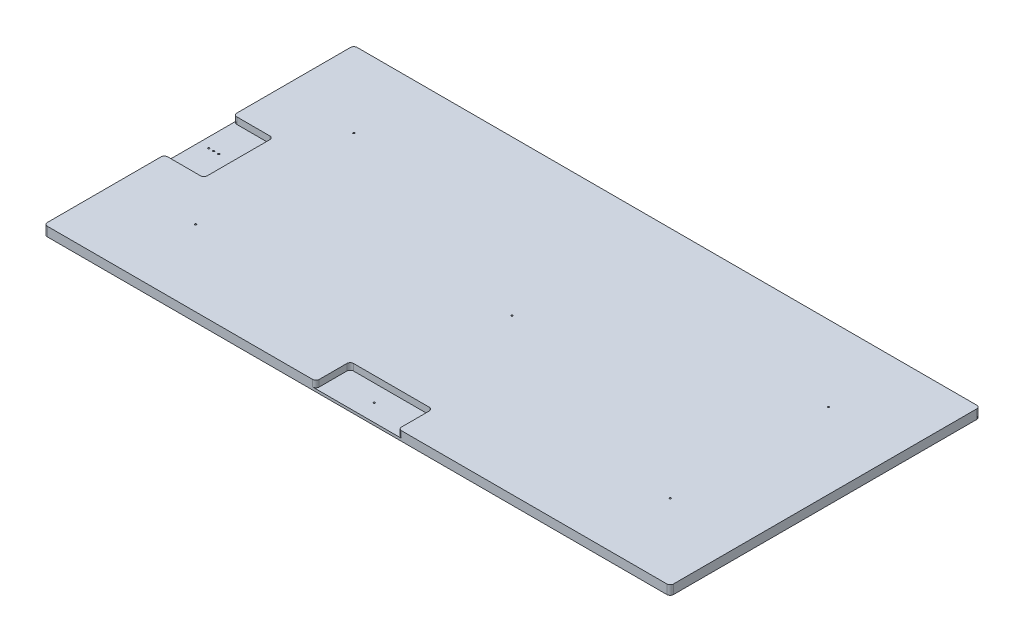
SolidWorks part; units mm, degrees
ref_plane "Front Plane" through (0, 0, 0) normal (0, 0, 1) x (1, 0, 0)
ref_plane "Top Plane" through (0, 0, 0) normal (0, 1, 0) x (1, 0, 0)
ref_plane "Right Plane" through (0, 0, 0) normal (1, 0, 0) x (0, 0, -1)
sketch "Sketch1" plane through (0, 0, 0) normal (0, 1, 0) x (1, 0, 0)
  line L1 (-603.25, -298.45) -> (603.25, -298.45)
  line L2 (-603.25, -298.45) -> (-603.25, 298.45)
  line L3 (-603.25, 298.45) -> (603.25, 298.45)
  line L4 (603.25, -298.45) -> (603.25, 298.45)
  line L5 (-603.25, -298.45) -> (603.25, 298.45) construction
  line L6 (-603.25, 298.45) -> (603.25, -298.45) construction
  point P0 (0, 0)
  dimension "D1" = 1206.5
  dimension "D2" = 596.9
extrude "Boss-Extrude1" add sketch "Sketch1" along normal blind 17.78
hole_wizard "1/8 (0.125) Diameter Hole1" positions "Sketch2" profile "Sketch3" hole size "1/8" standard "ANSI Inch" end condition through all
sketch "Sketch2" plane through (0, 17.78, 0) normal (0, 1, 0) x (1, 0, 0)
  line L1 (-457.2, -152.4) -> (457.2, -152.4) construction
  line L2 (-457.2, -152.4) -> (-457.2, 152.4) construction
  line L3 (-457.2, 152.4) -> (457.2, 152.4) construction
  line L4 (457.2, -152.4) -> (457.2, 152.4) construction
  line L5 (-457.2, -152.4) -> (457.2, 152.4) construction
  line L6 (-457.2, 152.4) -> (457.2, -152.4) construction
  point P0 (0, 0)
  point P1 (457.2, 152.4)
  point P50 (-457.2, -152.4)
  point P51 (-457.2, 152.4)
  point P52 (457.2, -152.4)
  point P63 (0, 0)
  dimension "D1" = 914.4
  dimension "D2" = 304.8
sketch "Sketch3" plane through (0, 17.78, 0) normal (1, 0, 0) x (0, 0, 1)
  line L0 (0, 0) -> (0, 17.78)
  line L1 (0, 17.78) -> (1.5875, 17.78)
  line L2 (1.5875, 17.78) -> (1.5875, 0)
  line L5 (1.5875, 0) -> (0, 0)
  line L11 (0, -6.35) -> (0, 107.95) construction
  dimension "Thru Hole Dia." = 3.175
  dimension "Thru Hole Depth" = 17.78
fillet "Fillet1" radius 6.35 4 edges at (603.25, 8.89, -298.45) (603.25, 8.89, 298.45) (-603.25, 8.89, 298.45) (-603.25, 8.89, -298.45)
sketch "Sketch4" plane through (0, 17.78, 0) normal (0, 1, 0) x (1, 0, 0)
  line L0 (0, 298.45) -> (0, -298.45) construction
  line L1 (596.9, 298.45) -> (-596.9, 298.45) construction
  line L2 (-596.9, -298.45) -> (596.9, -298.45) construction
  line L3 (-603.25, 0) -> (603.25, 0) construction
  line L4 (-79.375, -232.41) -> (79.375, -232.41)
  line L5 (-79.375, -232.41) -> (-79.375, -298.45)
  line L6 (-79.375, -298.45) -> (79.375, -298.45)
  line L7 (79.375, -232.41) -> (79.375, -298.45)
  line L8 (-79.375, -232.41) -> (79.375, -298.45) construction
  line L9 (-79.375, -298.45) -> (79.375, -232.41) construction
  line L10 (-603.25, 292.1) -> (-603.25, -292.1) construction
  line L11 (603.25, -292.1) -> (603.25, 292.1) construction
  line L13 (-527.05, 66.675) -> (-603.25, 66.675)
  line L14 (-527.05, 66.675) -> (-527.05, -66.675)
  line L15 (-527.05, -66.675) -> (-603.25, -66.675)
  line L16 (-603.25, 66.675) -> (-603.25, -66.675)
  line L17 (-527.05, 66.675) -> (-603.25, -66.675) construction
  line L18 (-527.05, -66.675) -> (-603.25, 66.675) construction
  point P6 (0, -265.43)
  point P17 (-565.15, 0)
  dimension "D1" = 158.75
  dimension "D2" = 66.04
  dimension "D3" = 133.35
  dimension "D4" = 76.2
extrude "Cut-Extrude1" cut sketch "Sketch4" against normal blind 12.7
fillet "Fillet2" radius 6.35 8 edges at (79.375, 11.43, 298.45) (-79.375, 11.43, 298.45) (-79.375, 11.43, 232.41) (79.375, 11.43, 232.41) (-603.25, 11.43, 66.675) (-603.25, 11.43, -66.675) (-527.05, 11.43, 66.675) (-527.05, 11.43, -66.675)
hole_wizard "1/8 (0.125) Diameter Hole2" positions "Sketch5" profile "Sketch6" hole size "1/8" standard "ANSI Inch"
sketch "Sketch5" plane through (0, 5.08, 0) normal (0, 1, 0) x (1, 0, 0)
  line L0 (-527.05, 0) -> (-603.25, 0) construction
  line L1 (-527.05, -60.325) -> (-527.05, 60.325) construction
  line L2 (-603.25, 73.025) -> (-603.25, -73.025) construction
  line L6 (-527.05, 0) -> (603.25, 0) construction
  line L7 (603.25, -292.1) -> (603.25, 292.1) construction
  point P8 (-565.15, 0)
  point P13 (-574.802, 0)
  point P14 (-584.454, 0)
  point P21 (0, -265.43)
  point P30 (577.85, 0)
  point P37 (568.325, 0)
  point P38 (558.8, 0)
  dimension "D1" = 3
  dimension "D2" = 25.4
  dimension "D3" = 3
sketch "Sketch6" plane through (558.8, 5.08, 0) normal (1, 0, 0) x (0, 0, 1)
  line L0 (0, 0) -> (0, 5.08)
  line L1 (0, 5.08) -> (1.5875, 5.08)
  line L2 (1.5875, 5.08) -> (1.5875, 0)
  line L5 (1.5875, 0) -> (0, 0)
  line L11 (0, -6.35) -> (0, 107.95) construction
  dimension "Thru Hole Dia." = 3.175
  dimension "Thru Hole Depth" = 5.08
